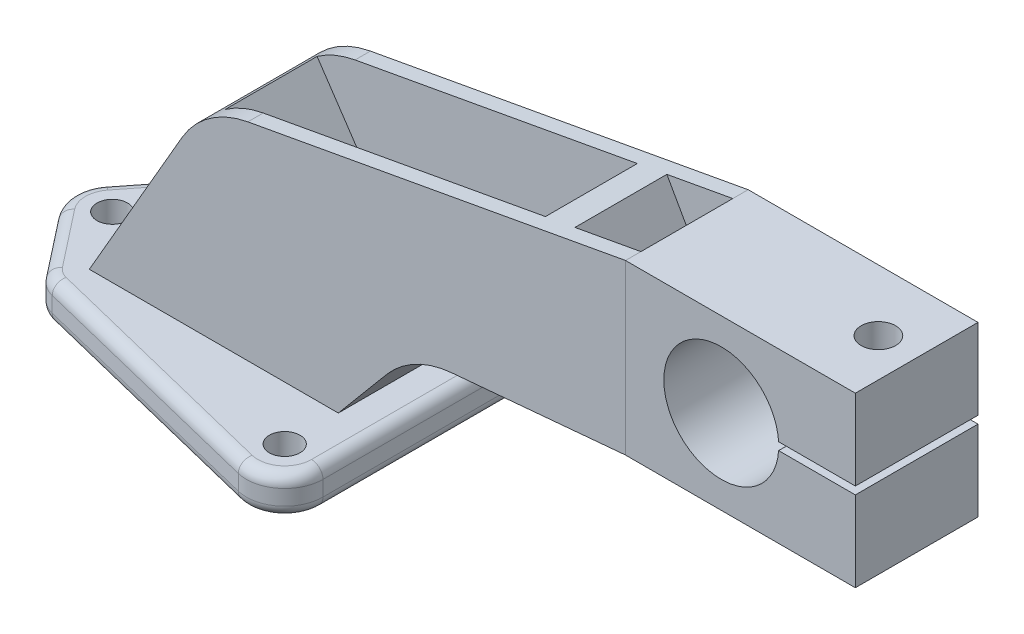
SolidWorks part; units mm, degrees
ref_plane "Front Plane" through (0, 0, 0) normal (0, 0, 1) x (1, 0, 0)
ref_plane "Top Plane" through (0, 0, 0) normal (0, 1, 0) x (1, 0, 0)
ref_plane "Right Plane" through (0, 0, 0) normal (1, 0, 0) x (0, 0, -1)
ref_plane "Plane1" through (0, 0, 16) normal (0, 0, 1) x (1, 0, 0)
sketch "Sketch1" plane through (0, 0, 16) normal (0, 0, 1) x (1, 0, 0)
  line L0 (0, 0) -> (82564.1702, 0) construction
  line L1 (0, 0) -> (0, -82564.1702) construction
  line L2 (75, 0) -> (75, -82564.1702) construction
  line L3 (200, 0) -> (200, -82564.1702) construction
  line L4 (175, 0) -> (175, -50000) construction
  line L5 (210, 72) -> (210, 28) construction
  line L6 (150, 72) -> (150, 28) construction
  line L7 (150, 72) -> (210, 72) construction
  line L8 (150, 28) -> (210, 28) construction
  line L9 (210, 50) -> (150, 50) construction
  line L10 (195.5, 72) -> (195.5, 28) construction
  line L11 (204.5, 72) -> (204.5, 28) construction
  circle A0 centre (175, 50) radius 15
  dimension "D8" = 30
  dimension "D1" = 75
  dimension "D2" = 200
  dimension "D3" = 25
  dimension "D6" = 44
  dimension "D7" = 72
  dimension "D4" = 10
  dimension "D5" = 60
  dimension "D9" = 4.5
  dimension "D10" = 9
sketch "Sketch2" plane through (0, 0, 16) normal (0, 0, 1) x (1, 0, 0)
  line L0 (10, 0) -> (34.2142, 41.9402)
  line L1 (-200000, 0) -> (282564.1702, 0) construction
  line L2 (51.3843, 54.0354) -> (150, 72)
  line L3 (150, 28) -> (104.5598, 23.907)
  line L4 (87.6515, 15.0775) -> (75, 0)
  line L5 (75, 200000) -> (75, -282564.1702) construction
  line L6 (75, 0) -> (10, 0)
  line L7 (150, 72) -> (150, 28)
  arc A0 (104.5598, 23.907) -> (87.6515, 15.0775) centre (106.8026, -0.9922) ccw
  arc A1 (34.2142, 41.9402) -> (51.3843, 54.0354) centre (55.8648, 29.4402) cw
  point P15 (94.2836, 22.9813)
  point P18 (40, 51.9615)
  dimension "D6" = 25
  dimension "D1" = 10
  dimension "D2" = 60
  dimension "D3" = 60
  dimension "D4" = 50
  dimension "D5" = 30
extrude "Boss-Extrude1" add sketch "Sketch2" against normal blind 4
mirror "Mirror2" about plane through (0, 0, 0) normal (0, 0, 1) of bodies 101
sketch "Sketch3" plane through (0, 0, 16) normal (0, 0, 1) x (1, 0, 0)
  line L0 (189.9666, 51) -> (210, 51)
  line L1 (150, 72) -> (210, 72)
  line L2 (150, 72) -> (150, 28)
  line L3 (150, 28) -> (210, 28)
  line L4 (210, 72) -> (210, 51)
  line L6 (210, 49) -> (189.9666, 49)
  line L7 (210, 50) -> (150, 50) construction
  line L8 (210, 49) -> (210, 28)
  arc A0 (189.9666, 51) -> (189.9666, 49) centre (175, 50) ccw
  circle A1 centre (175, 50) radius 15 construction
  dimension "D1" = 1
  dimension "D2" = 2
extrude "Boss-Extrude2" add sketch "Sketch3" against normal blind 32.01 and the other way blind 0.01
sketch "Sketch4" plane through (0, 72, 0) normal (0, 1, 0) x (1, 0, 0)
  line L0 (204.5, -16) -> (204.5, 16.01) construction
  line L1 (150, 16.01) -> (210, 16.01) construction
  line L2 (200, 0.005) -> (204.5, 0.005) construction
  circle A0 centre (200, 0.005) radius 4.5
  dimension "D1" = 9
extrude "Cut-Extrude1" cut sketch "Sketch4" against normal up to surface (23 mm away) contours A0 up to face at (199.9833, 49, 0)
sketch "Sketch5" plane through (0, 49, 0) normal (0, 1, 0) x (1, 0, 0)
  circle A0 centre (200, 0.005) radius 4
  circle A2 centre (200, 0.005) radius 4.5 construction
  dimension "D1" = 8
extrude "Cut-Extrude2" cut sketch "Sketch5" against normal through all both and the other way through all
sketch "Sketch6" plane through (0, 0, 0) normal (0, 1, 0) x (1, 0, 0)
  line L0 (-7.8704, 6.169) -> (3.7037, 20.9352)
  line L1 (8.0811, 23.7664) -> (72.6013, 39.7081)
  line L2 (85, 30) -> (85, -30)
  line L3 (72.6013, -39.7081) -> (8.0811, -23.7664)
  line L4 (3.7037, -20.9352) -> (-7.8704, -6.169)
  circle A0 centre (75, 30) radius 4
  circle A1 centre (75, -30) radius 4
  circle A2 centre (0, 0) radius 4
  arc A3 (-7.8704, 6.169) -> (-7.8704, -6.169) centre (0, 0) ccw
  arc A4 (85, 30) -> (72.6013, 39.7081) centre (75, 30) ccw
  arc A5 (72.6013, -39.7081) -> (85, -30) centre (75, -30) ccw
  arc A6 (8.0811, 23.7664) -> (3.7037, 20.9352) centre (10, 16) ccw
  arc A7 (3.7037, -20.9352) -> (8.0811, -23.7664) centre (10, -16) ccw
  dimension "D1" = 8
  dimension "D4" = 20
  dimension "D5" = 8
  dimension "D2" = 60
  dimension "D3" = 30
extrude "Boss-Extrude3" add sketch "Sketch6" against normal blind 10
fillet "Fillet1" radius 3 20 edges at (5.6553, -10, -22.7174) (40.3412, -10, -31.7373) (81.165, -10, -37.8736) (85, -10, 0) (81.165, -10, 37.8736) (40.3412, -10, 31.7373) (5.6553, -10, 22.7174) (-2.0834, -10, 13.5521) (-10, -10, 0) (5.6553, 0, -22.7174) (40.3412, 0, -31.7373) (81.165, 0, -37.8736) (85, 0, 0) (81.165, 0, 37.8736) (40.3412, 0, 31.7373) (5.6553, 0, 22.7174) (-2.0834, 0, 13.5521) (-10, 0, 0) (-2.0834, -10, -13.5521) (-2.0834, 0, -13.5521)
sketch "Sketch9" plane through (0, 0, 12) normal (0, 0, -1) x (-1, 0, 0)
  line L0 (-75, 0) -> (-41.4675, 49.8783)
  line L1 (-37.6622, 46.5768) -> (-68.9751, 0)
  line L2 (-10, 0) -> (-75, 0) construction
  line L3 (-125.0787, 67.4601) -> (-68.473, 0)
  line L4 (-75, 0) -> (-87.6515, 15.0775) construction
  line L5 (-150, 72) -> (-51.3843, 54.0354) construction
  line L6 (-75, 0) -> (-129.3482, 64.7697)
  line L7 (-132.7835, 68.8637) -> (-125.0787, 67.4601)
  line L8 (-75, 0) -> (-68.9751, 0)
  line L9 (-129.3482, 64.7697) -> (-150, 28)
  line L10 (-150, 28) -> (-150, 38.2104)
  line L11 (-150, 28) -> (-150, 72) construction
  line L12 (-150, 38.2104) -> (-132.7835, 68.8637)
  line L14 (-132.7835, 68.8637) -> (-129.3482, 64.7697) construction
  arc A0 (-34.2142, 41.9402) -> (-51.3843, 54.0354) centre (-55.8648, 29.4402) ccw construction
  line M5 (-75, 0) -> (-10, 0)
  arc M7 (-34.2142, 41.9402) -> (-51.3843, 54.0354) centre (-55.8648, 29.4402) ccw
  line M8 (-51.3843, 54.0354) -> (-150, 72)
  line M9 (-150, 72) -> (-150, 28)
  line M12 (-87.6515, 15.0775) -> (-75, 0)
  dimension "D1" = 5
  dimension "D2" = 5
  dimension "D3" = 5
extrude "Boss-Extrude6" add sketch "Sketch9" along normal up to surface (24 mm away) contours L6 L0 L3 M12 M8 | L3 L0 L1 M5 | L0 L3 L1 M7 | L14 L12 L9 M9
equation "\"D9@Sketch1\"=\"D10@Sketch1\"/2"
equation "\"p1_arg\"= 60"
equation "\"p1_mag\"= 60"
equation "\"D3@Sketch2\"=\"p1_mag\""
equation "\"p2_arg\"= 50"
equation "\"p2_mag\"= 30"
equation "\"clear\"= 10"
equation "\"D1@Sketch2\"=\"clear\""
equation "\"r1\"=25"
equation "\"D6@Sketch2\"=\"r1\""
equation "\"TH\"= 5"
equation "\"D2@Sketch2\"=\"p1_arg\""
equation "\"D4@Sketch2\"=\"p2_arg\""
equation "\"D5@Sketch2\"=\"p2_mag\""
equation "\"D1@Sketch9\"=\"TH\""
equation "\"D2@Sketch9\"=\"TH\""
equation "\"D3@Sketch9\"=\"TH\""
